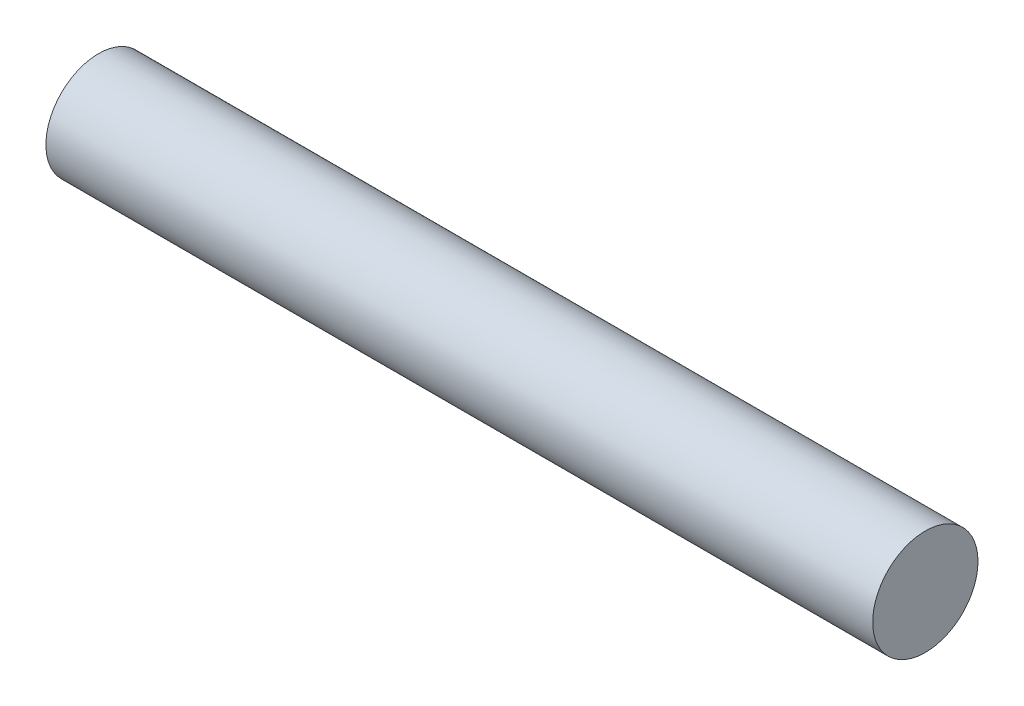
SolidWorks part; units mm, degrees
material "6061-T6 (SS)"
ref_plane "Front Plane" through (0, 0, 0) normal (1, 0, 0) x (0, 1, 0)
ref_plane "Top Plane" through (0, 0, 0) normal (0, 0, 1) x (0, 1, 0)
ref_plane "Right Plane" through (0, 0, 0) normal (0, 1, 0) x (-1, 0, 0)
sketch "Sketch2" plane through (0, 0, 0) normal (1, 0, 0) x (0, 1, 0)
  circle A0 centre (0, 0) radius 12.7
  dimension "D1" = 25.4
extrude "Boss-Extrude1" add sketch "Sketch2" along normal blind 199.39
equation "\"d\"= 1'diameter of the bar [in]"
equation "\"area\"= pi * ( \"r\" ^ 2 )'cross sectional area [in^2]"
equation "\"F\"= 500'Lead [pound force]"
equation "\"del\"= 0.009'max deflection [in]"
equation "\"E\"= 10000000'Youngs modulus of El. [psi]"
equation "\"L\"= \"del\" * \"area\" * \"E\" / \"F\"'designed length"
equation "\"r\"= \"d\" / 2'radius of the bar [in]"
